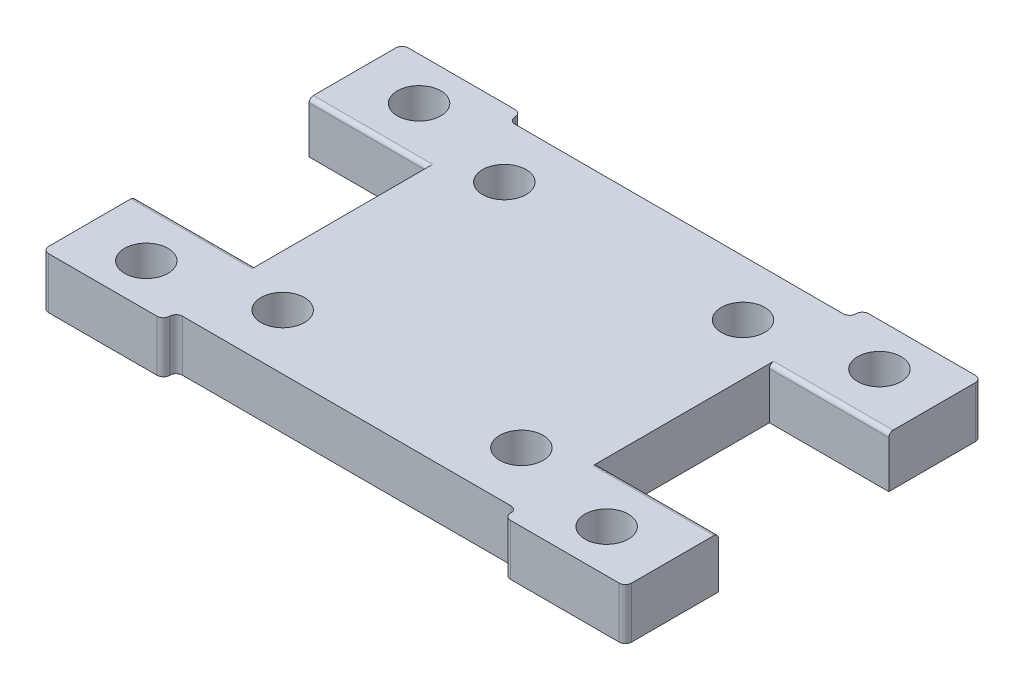
SolidWorks part; units mm, degrees
material "Alloy Steel"
ref_plane "Front Plane" through (0, 0, 0) normal (0, 0, 1) x (1, 0, 0)
ref_plane "Top Plane" through (0, 0, 0) normal (0, 1, 0) x (1, 0, 0)
ref_plane "Right Plane" through (0, 0, 0) normal (1, 0, 0) x (0, 0, -1)
sketch "Sketch1" plane through (0, 0, 0) normal (0, 1, 0) x (1, 0, 0)
  line L0 (20, 19.5) -> (20, -19.5) construction
  line L1 (-19.26, -19.5) -> (19.26, -19.5)
  line L3 (-19.26, 19.5) -> (19.26, 19.5)
  line L5 (20, 20.24) -> (20, 20.26)
  line L7 (20.74, 21) -> (34, 21)
  line L8 (20, 19.5) -> (-20, -19.5) construction
  line L9 (-20, 19.5) -> (20, -19.5) construction
  line L10 (0, 0) -> (0, 19.5) construction
  line L11 (0, 0) -> (-20, 0) construction
  line L13 (34.2, -21) -> (20.74, -21)
  line L14 (20, -20.26) -> (20, -20.24)
  line L16 (20, 10.1) -> (34, 10.1)
  line L18 (34.2, -10.099) -> (20, -10.099)
  line L19 (20, -10.099) -> (20, 10.1)
  line L20 (-20, 19.5) -> (-20, -19.5) construction
  line L21 (-20, -10.099) -> (-20, 10.1)
  line L22 (-34.2, -10.099) -> (-20, -10.099)
  line L24 (-20, 10.1) -> (-34, 10.1)
  line L25 (-20, -20.26) -> (-20, -20.24)
  line L26 (-34.2, -21) -> (-20.74, -21)
  line L28 (-20.74, 21) -> (-34, 21)
  line L29 (-20, 20.24) -> (-20, 20.26)
  line L30 (34, 10.1) -> (34, 21)
  line L31 (34.2, -10.099) -> (34.2, -21)
  line L32 (-34.2, -10.099) -> (-34.2, -21)
  line L33 (-34, 10.1) -> (-34, 21)
  circle A0 centre (-14, 13) radius 2.55
  circle A1 centre (14, 13) radius 2.55
  circle A2 centre (14, -13) radius 2.55
  circle A3 centre (-14, -13) radius 2.55
  circle A4 centre (27, 16) radius 2.55
  circle A5 centre (27, -16) radius 2.55
  circle A6 centre (-27, -16) radius 2.55
  circle A7 centre (-27, 16) radius 2.55
  arc A12 (-20.74, 21) -> (-20, 20.26) centre (-20.74, 20.26) cw
  arc A13 (-20, 20.24) -> (-19.26, 19.5) centre (-19.26, 20.24) ccw
  arc A14 (20, 20.26) -> (20.74, 21) centre (20.74, 20.26) cw
  arc A15 (19.26, 19.5) -> (20, 20.24) centre (19.26, 20.24) ccw
  arc A16 (19.26, -19.5) -> (20, -20.24) centre (19.26, -20.24) cw
  arc A17 (20.74, -21) -> (20, -20.26) centre (20.74, -20.26) cw
  arc A18 (-20, -20.26) -> (-20.74, -21) centre (-20.74, -20.26) cw
  arc A19 (-19.26, -19.5) -> (-20, -20.24) centre (-19.26, -20.24) ccw
  point P0 (0, 0)
  point P46 (27, 10.1)
  point P48 (36, 21)
  point P51 (36, -21)
  point P54 (-36, -21)
  point P57 (-36, 21)
  point P60 (-20, 21)
  point P66 (20, 21)
  point P75 (20, -21)
  point P78 (-20, -21)
  dimension "D5" = 5.1
  dimension "D12" = 20.2
  dimension "D9" = 5.1
  dimension "D1" = 1.5
  dimension "D2" = 39
  dimension "D3" = 40
  dimension "D4" = 1.5
  dimension "D6" = 14
  dimension "D7" = 6.5
  dimension "D8" = 16
  dimension "D10" = 16
  dimension "D11" = 14
extrude "Boss-Extrude1" add sketch "Sketch1" along normal blind 6
fillet "Fillet1" radius 0.74 4 edges at (-34, 3, -21) (-34.2, 3, 21) (34.2, 3, 21) (34, 3, -21)
fillet "Fillet2" radius 0.5 4 edges at (-27, 6, -10.1) (-27.1, 6, 10.099) (27, 6, -10.1) (27.1, 6, 10.099)
